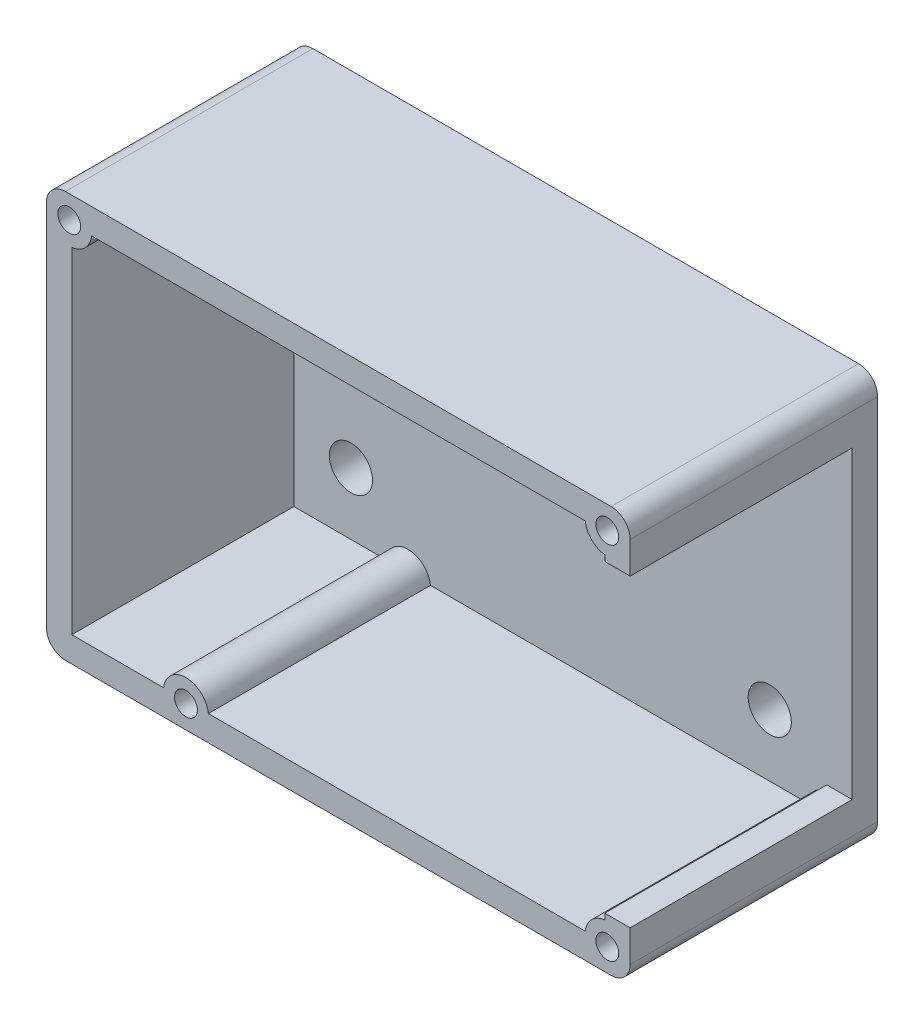
SolidWorks part; units mm, degrees
material "AISI 1020"
ref_plane "Front Plane" through (0, 0, 0) normal (0, 0, 1) x (1, 0, 0)
ref_plane "Top Plane" through (0, 0, 0) normal (0, 1, 0) x (1, 0, 0)
ref_plane "Right Plane" through (0, 0, 0) normal (1, 0, 0) x (0, 0, -1)
sketch "Sketch2" plane through (0, 0, 0) normal (0, 0, 1) x (1, 0, 0)
  line L1 (0, 0) -> (-46, 0)
  line L2 (0, 0) -> (0, -32)
  line L3 (0, -32) -> (-46, -32)
  line L4 (-46, 0) -> (-46, -32)
  dimension "D1" = 32
  dimension "D2" = 46
extrude "Boss-Extrude1" add sketch "Sketch2" along normal blind 19.5
shell "Shell1" thickness 2
sketch "Sketch3" plane through (0, 0, 0) normal (0, 0, -1) x (-1, 0, 0)
  line L0 (0, -32) -> (0, 0) construction
  line L1 (0, 0) -> (46, 0) construction
  point P0 (6.5, -7)
  point P1 (6.5, -25.1149)
  point P2 (39.5, -25.1149)
  point P3 (39.5, -7)
  dimension "D1" = 6.5
  dimension "D2" = 7
  dimension "D3" = 33
hole_wizard "CBORE for M3 SBHCS1" positions "Sketch4" profile "Sketch5" counterbore size "M3" standard "ANSI Metric"
sketch "Sketch4" plane through (0, 0, 0) normal (0, 0, -1) x (-1, 0, 0)
  point P0 (6.5, -7)
  point P3 (6.5, -25.1149)
  point P6 (39.5, -25.1149)
  point P9 (39.5, -7)
sketch "Sketch5" plane through (-6.5, -7, 0) normal (1, 0, 0) x (0, 1, 0)
  line L0 (0, 0) -> (0, 3.0215)
  line L1 (0, 3.0215) -> (1.7, 2)
  line L2 (1.7, 2) -> (1.7, 1.65)
  line L3 (1.7, 1.65) -> (3.35, 1.65)
  line L5 (3.35, 1.65) -> (3.35, 0.025)
  line L6 (3.35, 0.025) -> (3.375, 0)
  line L7 (3.375, 0) -> (0, 0)
  line L8 (-3.35, 0.025) -> (-3.375, 0) construction
  line L10 (0, 3.0215) -> (-1.7, 2) construction
  line L11 (0, -6.35) -> (0, 107.95) construction
  dimension "Hole Dia." = 3.4
  dimension "Hole Depth" = 2
  dimension "C'Bore Dia." = 6.7
  dimension "C'Bore Depth" = 1.65
  dimension "Near C'Sink Dia." = 6.75
  dimension "Near C'Sink Angle" = 90
  dimension "Drill Angle" = 118
sketch "Sketch8" plane through (0, 0, 1.65) normal (0, 0, -1) x (-1, 0, 0)
  circle A0 centre (6.5, -25.1149) radius 3.35 construction
  circle A1 centre (39.5, -25.1149) radius 3.35 construction
  circle A2 centre (39.5, -7) radius 3.35 construction
  circle A3 centre (6.5, -7) radius 3.35 construction
  circle A4 centre (6.5, -25.1149) radius 3.35
  circle A5 centre (39.5, -25.1149) radius 3.35
  circle A6 centre (39.5, -7) radius 3.35
  circle A7 centre (6.5, -7) radius 3.35
  circle A8 centre (6.5, -25.1149) radius 1.7 construction
  circle A9 centre (39.5, -25.1149) radius 1.7 construction
  circle A10 centre (39.5, -7) radius 1.7 construction
  circle A11 centre (6.5, -7) radius 1.7 construction
  circle A12 centre (6.5, -25.1149) radius 1.7
  circle A13 centre (39.5, -25.1149) radius 1.7
  circle A14 centre (39.5, -7) radius 1.7
  circle A15 centre (6.5, -7) radius 1.7
extrude "Boss-Extrude2" add sketch "Sketch8" along normal blind 3.63 and the other way up to surface
sketch "Sketch9" plane through (0, 0, 0) normal (0, 0, -1) x (-1, 0, 0)
  line L0 (0, 0) -> (46, 0) construction
  line L2 (0, -32) -> (0, 0) construction
  circle A0 centre (15.5, -16) radius 5
  dimension "D1" = 10
  dimension "D2" = 16
  dimension "D3" = 15.5
extrude "Boss-Extrude3" add sketch "Sketch9" along normal blind 2
sketch "Sketch10" plane through (0, 0, 0) normal (1, 0, 0) x (0, 0, -1)
  line L0 (-19.5, -4) -> (-2, -4)
  line L1 (-19.5, -32) -> (-19.5, 0) construction
  line L2 (0, -32) -> (0, 0) construction
  line L4 (-2, -28) -> (-19.5, -28)
  line L5 (-19.5, -28) -> (-19.5, -4)
  line L6 (-19.5, 0) -> (0, 0) construction
  line L7 (-19.5, -32) -> (0, -32) construction
  line L8 (-2, -4) -> (-2, -28)
  dimension "D1" = 4
  dimension "D2" = 4
  dimension "D3" = 2
extrude "Cut-Extrude1" cut sketch "Sketch10" against normal up to surface (2 mm away) up to face at (-2, -16, 10.75)
sketch "Sketch11" plane through (0, 0, 0) normal (0, 0, -1) x (-1, 0, 0)
  line L4 (0, -32) -> (0, 0) construction
  line L5 (0, 0) -> (46, 0) construction
  line L6 (46, 0) -> (46, -32) construction
  line L7 (46, -32) -> (0, -32) construction
  point P0 (1.8, -1.8)
  point P1 (35.05, -1.8)
  point P2 (1.8, -30.2)
  point P3 (44.2, -30.2)
  dimension "D1" = 1.8
  dimension "D2" = 1.8
  dimension "D3" = 4.45
  dimension "D4" = 1.8
  dimension "D5" = 1.8
hole_wizard "CBORE for M1.6 SHCS1" positions "Sketch12" profile "Sketch13" counterbore size "M1.6" standard "ANSI Metric" end condition through all
sketch "Sketch12" plane through (0, 0, 0) normal (0, 0, -1) x (-1, 0, 0)
  line L1 (46, 0) -> (46, -32) construction
  point P0 (1.8, -1.8)
  point P3 (44.2, -1.8)
  point P6 (35, -30.2)
  point P9 (1.8, -30.2)
  dimension "D1" = 1.8
  dimension "D2" = 4.5
sketch "Sketch13" plane through (-1.8, -1.8, 0) normal (1, 0, 0) x (0, 1, 0)
  line L0 (0, 0) -> (0, 19.5)
  line L1 (0, 19.5) -> (0.9, 19.5)
  line L3 (0.9, 19.5) -> (0.9, 1.6)
  line L4 (1.75, 1.6) -> (0.9, 1.6)
  line L5 (1.75, 1.6) -> (1.75, 0.025)
  line L6 (1.75, 0.025) -> (1.775, 0)
  line L7 (1.775, 0) -> (0, 0)
  line L8 (-1.75, 0.025) -> (-1.775, 0) construction
  line L11 (0, -6.35) -> (0, 107.95) construction
  dimension "Thru Hole Dia." = 1.8
  dimension "Thru Hole Depth" = 19.5
  dimension "C'Bore Dia." = 3.5
  dimension "C'Bore Depth" = 1.6
  dimension "Near C'Sink Dia." = 3.55
  dimension "Near C'Sink Angle" = 90
sketch "Sketch14" plane through (0, 0, 1.6) normal (0, 0, -1) x (-1, 0, 0)
  circle A0 centre (35, -30.2) radius 0.9 construction
  circle A1 centre (1.8, -1.8) radius 1.75
  circle A2 centre (1.8, -1.8) radius 1.75
  circle A3 centre (1.8, -1.8) radius 0.9
  circle A4 centre (1.8, -1.8) radius 0.9
  circle A5 centre (44.2, -1.8) radius 0.9 construction
  circle A6 centre (44.2, -1.8) radius 1.775 construction
  circle A8 centre (35, -30.2) radius 1.775 construction
  circle A9 centre (1.8, -30.2) radius 0.9 construction
  circle A10 centre (1.8, -30.2) radius 1.75 construction
  circle A11 centre (35, -30.2) radius 0.9
  circle A12 centre (44.2, -1.8) radius 0.9
  circle A13 centre (44.2, -1.8) radius 1.775
  arc A14 (43.3225, -30) -> (44, -29.3225) centre (44.2, -30.2) ccw
  circle A15 centre (35, -30.2) radius 1.775
  circle A16 centre (1.8, -30.2) radius 0.9
  circle A17 centre (1.8, -30.2) radius 1.75
  dimension "D1" = 0
  dimension "D2" = 0
extrude "Boss-Extrude4" add sketch "Sketch14" against normal up to surface (17.9 mm away) contours A13 A12 | A17 A16 | A15 A11
fillet "Fillet1" radius 1.5 4 edges at (0, 0, 9.75) (-46, 0, 9.75) (-46, -32, 9.75) (0, -32, 9.75)
sketch "Sketch15" plane through (-46, 0, 0) normal (-1, 0, 0) x (0, 0, 1)
  line L0 (21.5, -30.5) -> (21.5, -1.5) construction
  line L1 (0, 0) -> (19.5, 0) construction
  point P0 (9, -13)
  dimension "D1" = 12.5
  dimension "D2" = 13
